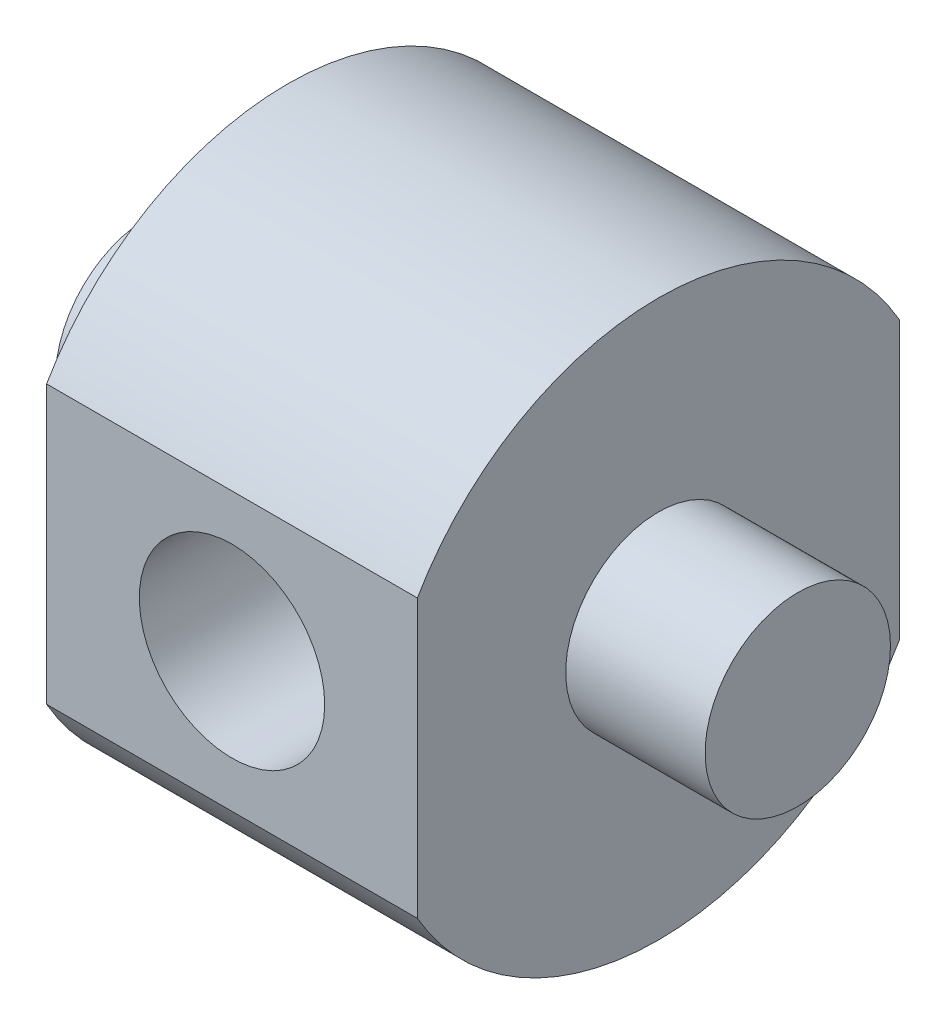
SolidWorks part; units mm, degrees
ref_plane "Front Plane" through (0, 0, 0) normal (0, 0, 1) x (1, 0, 0)
ref_plane "Top Plane" through (0, 0, 0) normal (0, 1, 0) x (1, 0, 0)
ref_plane "Right Plane" through (0, 0, 0) normal (1, 0, 0) x (0, 0, -1)
sketch "Sketch1" plane through (0, 0, 0) normal (1, 0, 0) x (0, 0, -1)
  circle A0 centre (0, 0) radius 9.525
  dimension "D1" = 19.05
extrude "Boss-Extrude1" add sketch "Sketch1" along normal mid plane 12.7
sketch "Sketch2" plane through (6.35, 0, 0) normal (1, 0, 0) x (0, 0, -1)
  circle A1 centre (0, 0) radius 3.175
  dimension "D1" = 6.35
extrude "Boss-Extrude2" add sketch "Sketch2" along normal blind 4.7752
mirror "Mirror1" about plane through (0, 0, 0) normal (1, 0, 0) of "Boss-Extrude2"
sketch "Sketch3" plane through (6.35, 0, 0) normal (1, 0, 0) x (0, 0, -1)
  line L1 (-15.5157, 9.4996) -> (-8.255, 9.4996)
  line L2 (-15.5157, 9.4996) -> (-15.5157, -10.2079)
  line L3 (-15.5157, -10.2079) -> (-8.255, -10.2079)
  line L4 (-8.255, 9.4996) -> (-8.255, -10.2079)
  line L5 (14.2001, 9.1454) -> (8.255, 9.1454)
  line L6 (14.2001, 9.1454) -> (14.2001, -10.5368)
  line L7 (14.2001, -10.5368) -> (8.255, -10.5368)
  line L8 (8.255, 9.1454) -> (8.255, -10.5368)
  dimension "D1" = 16.51
  dimension "D2" = 8.255
extrude "Cut-Extrude1" cut sketch "Sketch3" against normal through all both and the other way through all
sketch "Sketch4" plane through (0, 0, 8.255) normal (0, 0, 1) x (1, 0, 0)
  circle A0 centre (0, 0) radius 3.175
  dimension "D1" = 6.35
extrude "Cut-Extrude2" cut sketch "Sketch4" against normal through all both and the other way through all
